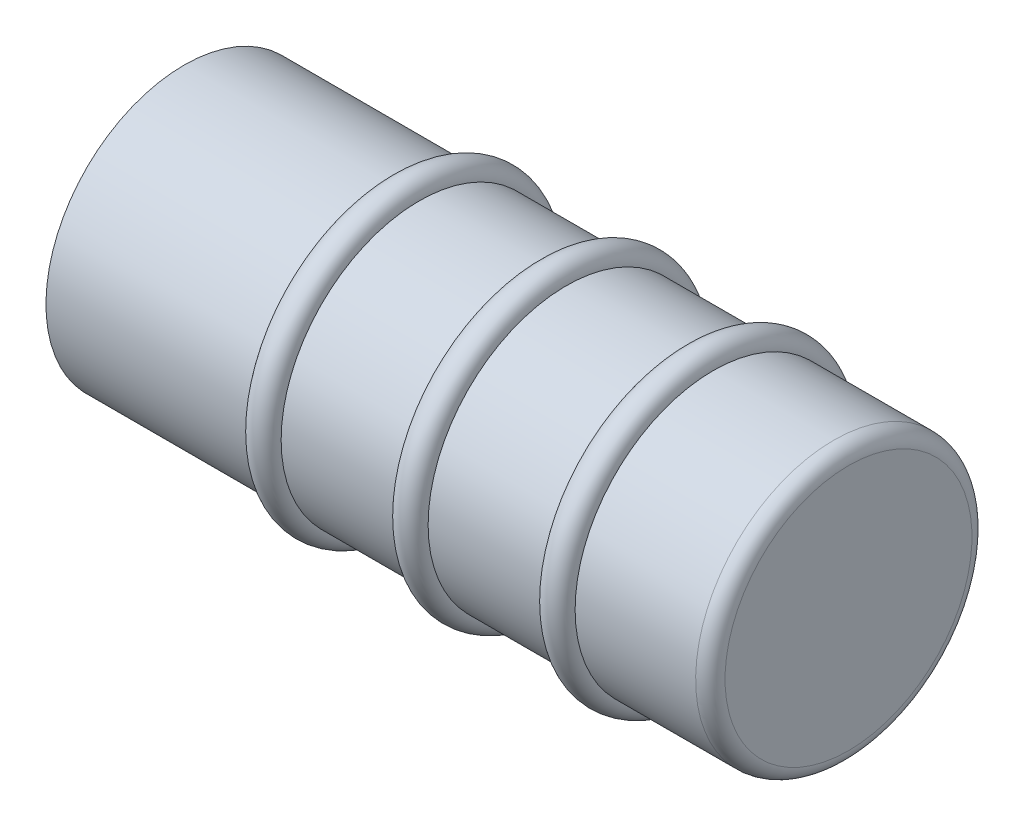
SolidWorks part; units mm, degrees
ref_plane "Front" through (0, 0, 0) normal (0, 0, 1) x (1, 0, 0)
ref_plane "Top" through (0, 0, 0) normal (0, 1, 0) x (1, 0, 0)
ref_plane "Right" through (0, 0, 0) normal (1, 0, 0) x (0, 0, -1)
sketch "Sketch1" plane through (0, 0, 0) normal (0, 0, 1) x (1, 0, 0)
  line L0 (-22.6, 4.7) -> (-22.6, 0)
  line L5 (-22.6, 4.7) -> (-0.5, 4.7)
  line L6 (0, 4.2) -> (0, 0)
  line L7 (0, 0) -> (-22.6, 0)
  line L8 (-22.6, 0) -> (0, 0) construction
  arc A0 (-0.5, 4.7) -> (0, 4.2) centre (-0.5, 4.2) cw
  point P4 (0, 4.7)
  dimension "D3" = 0.5
  dimension "D1" = 4.7
  dimension "D2" = 22.6
revolve "Revolve1" add sketch "Sketch1" angle 360 about L7
sketch "Sketch2" plane through (0, 0, 0) normal (0, 0, 1) x (1, 0, 0)
  line L0 (-0.5, 4.7) -> (-22.6, 4.7) construction
  line L1 (-22.6, 0) -> (0, 0) construction
  line L2 (-22.6, 4.7) -> (-22.6, -4.7) construction
  circle A0 centre (-15.1, 4.7) radius 0.5
  dimension "D1" = 1
  dimension "D2" = 7.5
revolve "Revolve2" add sketch "Sketch2" angle 360 about L1
pattern_linear "LPattern1" count 3 spacing 5 along (1, 0, 0) of "Revolve2"
